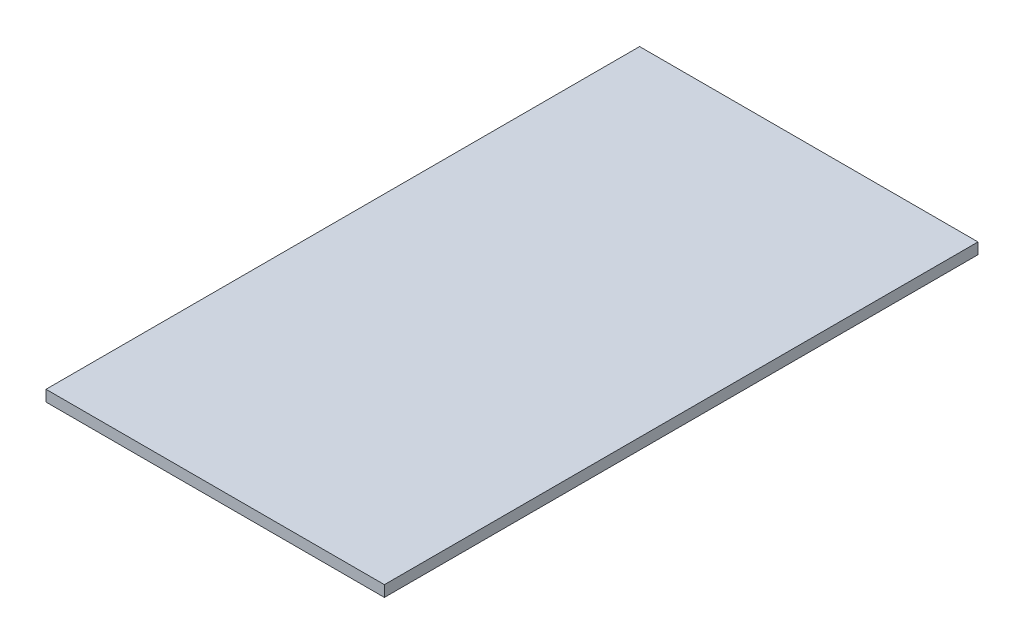
SolidWorks part; units mm, degrees
ref_plane "Plan de face" through (0, 0, 0) normal (0, 0, 1) x (1, 0, 0)
ref_plane "Plan de dessus" through (0, 0, 0) normal (0, 1, 0) x (1, 0, 0)
ref_plane "Plan de droite" through (0, 0, 0) normal (1, 0, 0) x (0, 0, -1)
sketch "Esquisse1" plane through (0, 0, 0) normal (0, 1, 0) x (1, 0, 0)
  line L1 (30.5, -53.5) -> (-30.5, -53.5)
  line L2 (30.5, -53.5) -> (30.5, 53.5)
  line L3 (30.5, 53.5) -> (-30.5, 53.5)
  line L4 (-30.5, -53.5) -> (-30.5, 53.5)
  line L5 (30.5, -53.5) -> (-30.5, 53.5) construction
  line L6 (30.5, 53.5) -> (-30.5, -53.5) construction
  point P0 (0, 0)
  dimension "D1" = 61
  dimension "D2" = 107
extrude "Boss.-Extru.1" add sketch "Esquisse1" along normal blind 2
